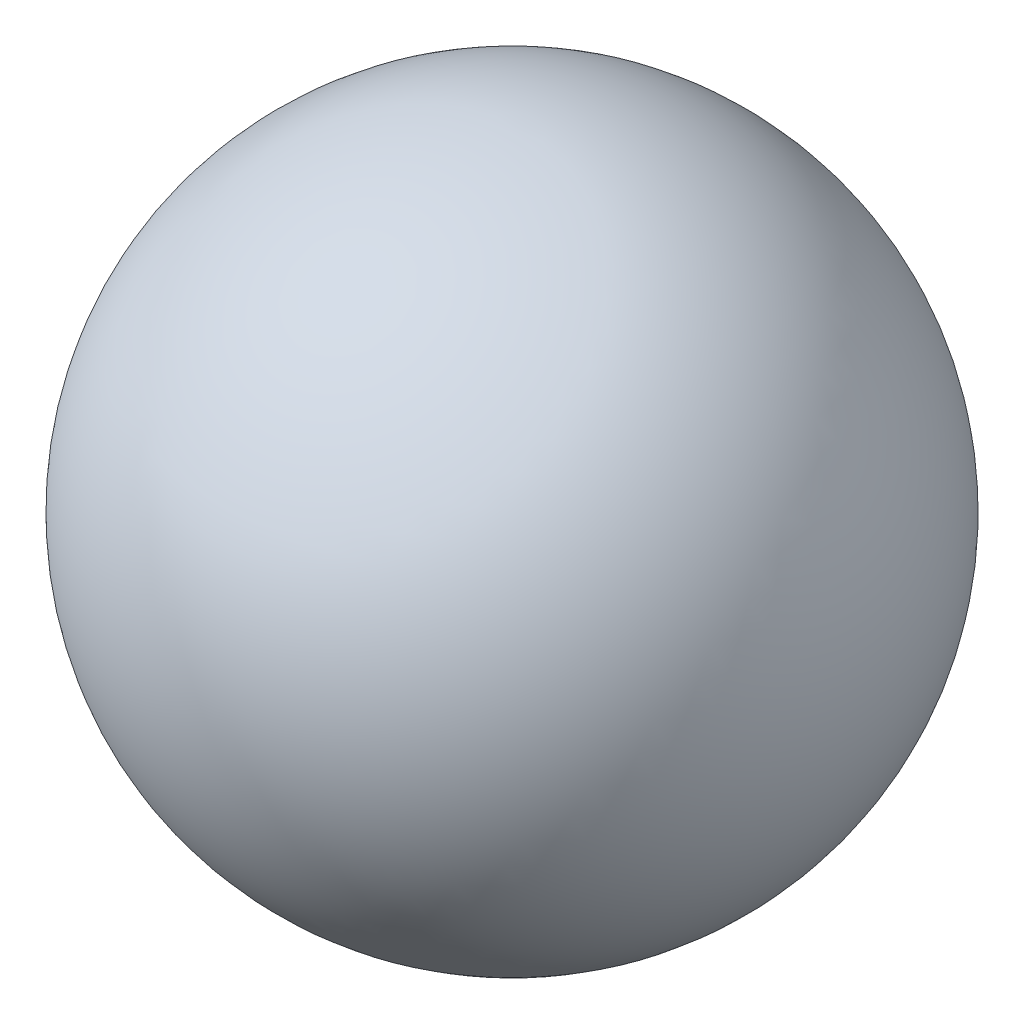
SolidWorks part; units mm, degrees
ref_plane "Ön Düzlem" through (0, 0, 0) normal (0, 0, 1) x (1, 0, 0)
ref_plane "Üst Düzlem" through (0, 0, 0) normal (0, 1, 0) x (1, 0, 0)
ref_plane "Sağ Düzlem" through (0, 0, 0) normal (1, 0, 0) x (0, 0, -1)
sketch "Çizim1" plane through (0, 0, 0) normal (0, 0, 1) x (1, 0, 0)
  line L0 (0, 20) -> (0, -20)
  arc A0 (0, -20) -> (0, 20) centre (0, 0) ccw
revolve "Döndür1" add sketch "Çizim1" angle 360 about L0
sketch "Çizim2" plane through (0, 0, 0) normal (0, 0, 1) x (1, 0, 0)
  line L0 (-8.7178, -18) -> (8.7178, -18)
  circle A0 centre (0, 0) radius 20 construction
  dimension "D1" = 18
extrude "Kes-Ekstrüzyon1" cut sketch "Çizim2" against normal through all both and the other way through all flip side to cut
hole_wizard "M10 Dişli Delik1" positions "Çizim3" profile "Çizim4" tap size "M10" standard "DIN"
sketch "Çizim3" plane through (0, -18, 0) normal (0, -1, 0) x (-1, 0, 0)
  point P0 (0, 0)
  point P3 (0, 0)
sketch "Çizim4" plane through (0, -18, 0) normal (1, 0, 0) x (0, 0, -1)
  line L0 (0, 0) -> (0, 12.5537)
  line L1 (0, 12.5537) -> (4.25, 10)
  line L2 (4.25, 10) -> (4.25, 0)
  line L5 (4.25, 0) -> (0, 0)
  line L10 (0, 12.5537) -> (-4.25, 10) construction
  line L11 (0, -6.35) -> (0, 107.95) construction
  dimension "Tap Drill Dia." = 8.5
  dimension "Tap Drill Depth" = 10
  dimension "Drill Angle" = 118
cosmetic thread "Delik Dişi1" parameters "D1"=10, "D2"=10
cosmetic thread "Delik Dişi2" parameters "D1"=10, "D2"=10
